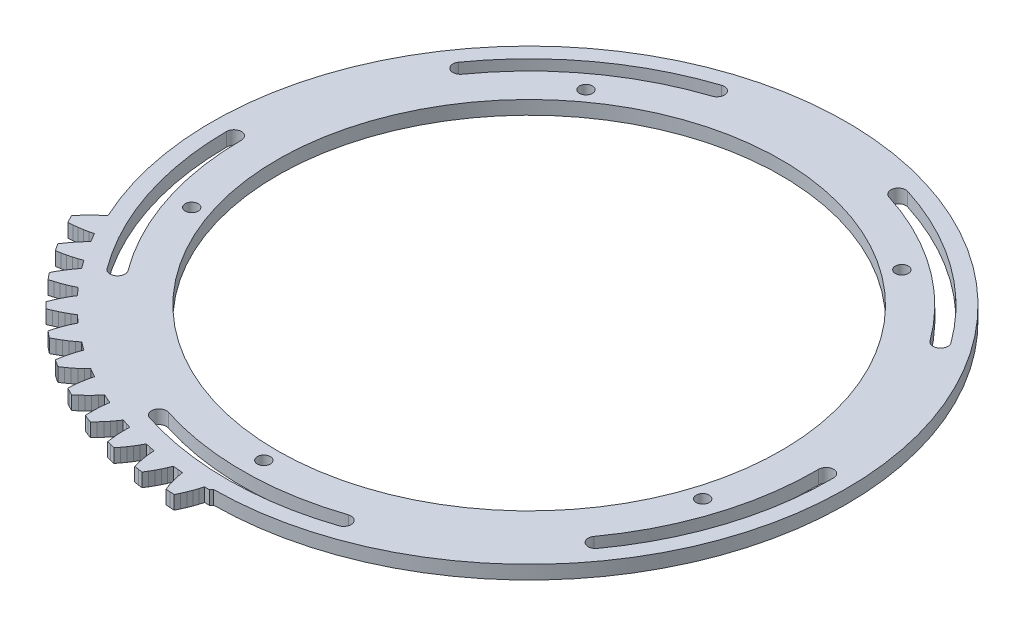
SolidWorks part; units mm, degrees
ref_plane "Front Plane" through (0, 0, 0) normal (0, 0, 1) x (1, 0, 0)
ref_plane "Top Plane" through (0, 0, 0) normal (0, 1, 0) x (1, 0, 0)
ref_plane "Right Plane" through (0, 0, 0) normal (1, 0, 0) x (0, 0, -1)
sketch "Sketch1" plane through (0, 0, 0) normal (0, 1, 0) x (1, 0, 0)
  line L0 (-111.5454, -37.0091) -> (0, 0) construction
  line L1 (0, 0) -> (-76.7897, 104.3262) construction
  line L2 (0, 0) -> (75.4908, 105.2699) construction
  line L3 (0, 0) -> (123.4456, -39.2658) construction
  line L4 (0, 0) -> (0.8028, -129.5375) construction
  circle A0 centre (0, 0) radius 139.7
  circle A1 centre (0, 0) radius 110.9007
  arc A2 (-129.5393, -0.4293) -> (-104.1044, -77.0902) centre (0, 0) ccw construction
  arc A3 (-132.8393, -0.4403) -> (-106.7564, -79.054) centre (0, 0) ccw
  arc A4 (-126.2393, -0.4184) -> (-101.4523, -75.1263) centre (0, 0) ccw
  arc A5 (-126.2393, -0.4184) -> (-132.8393, -0.4403) centre (-129.5393, -0.4293) ccw
  arc A6 (-106.7564, -79.054) -> (-101.4523, -75.1263) centre (-104.1044, -77.0902) ccw
  arc A7 (-40.4381, 123.0665) -> (-105.4871, 75.187) centre (0, 0) ccw construction
  arc A8 (-41.4683, 126.2016) -> (-108.1744, 77.1023) centre (0, 0) ccw
  arc A9 (-39.408, 119.9314) -> (-102.7999, 73.2716) centre (0, 0) ccw
  arc A10 (-39.408, 119.9314) -> (-41.4683, 126.2016) centre (-40.4381, 123.0665) ccw
  arc A11 (-108.1744, 77.1023) -> (-102.7999, 73.2716) centre (-105.4871, 75.187) ccw
  arc A12 (104.5471, 76.4886) -> (38.9097, 123.5583) centre (0, 0) ccw construction
  arc A13 (107.2105, 78.4371) -> (39.9009, 126.7059) centre (0, 0) ccw
  arc A14 (101.8838, 74.5401) -> (37.9185, 120.4106) centre (0, 0) ccw
  arc A15 (101.8838, 74.5401) -> (107.2105, 78.4371) centre (104.5471, 76.4886) ccw
  arc A16 (39.9009, 126.7059) -> (37.9185, 120.4106) centre (38.9097, 123.5583) ccw
  arc A17 (105.0518, -75.794) -> (129.5347, 1.1763) centre (0, 0) ccw construction
  arc A18 (107.728, -77.7248) -> (132.8345, 1.2062) centre (0, 0) ccw
  arc A19 (102.3757, -73.8631) -> (126.2348, 1.1463) centre (0, 0) ccw
  arc A20 (102.3757, -73.8631) -> (107.728, -77.7248) centre (105.0518, -75.794) ccw
  arc A21 (132.8345, 1.2062) -> (126.2348, 1.1463) centre (129.5347, 1.1763) ccw
  arc A22 (-39.6215, -123.3319) -> (41.1471, -122.8313) centre (0, 0) ccw construction
  arc A23 (-40.6309, -126.4737) -> (42.1953, -125.9604) centre (0, 0) ccw
  arc A24 (-38.6122, -120.19) -> (40.0989, -119.7022) centre (0, 0) ccw
  arc A25 (-38.6122, -120.19) -> (-40.6309, -126.4737) centre (-39.6215, -123.3319) ccw
  arc A26 (42.1953, -125.9604) -> (40.0989, -119.7022) centre (41.1471, -122.8313) ccw
  circle A27 centre (-111.5454, -37.0091) radius 2.8585
  circle A28 centre (-69.6672, 94.6496) radius 2.8585
  circle A29 centre (68.4887, 95.5058) radius 2.8585
  circle A30 centre (111.9956, -35.6238) radius 2.8585
  circle A31 centre (0.7283, -117.5225) radius 2.8585
  point P6 (-122.9494, -40.7928)
  point P15 (-76.7897, 104.3262)
  point P22 (75.4908, 105.2699)
  point P29 (123.4456, -39.2658)
  point P36 (0.8028, -129.5375)
  point P41 (0, 0)
  point P55 (0, 0)
  dimension "D2" = 5
extrude "Boss-Extrude1" add sketch "Sketch1" along normal blind 6
sketch "Sketch3" plane through (0, 0, 0) normal (0, 1, 0) x (1, 0, 0)
  line L0 (-95.7738, -103.0452) -> (-97.4797, -104.1074)
  line L1 (-97.4797, -104.1074) -> (-99.2611, -105.0958)
  line L2 (-99.2611, -105.0958) -> (-101.1089, -106.0174)
  line L3 (-101.1089, -106.0174) -> (-103.0168, -106.8763)
  line L4 (-103.0168, -106.8763) -> (-104.9804, -107.6753)
  line L5 (-104.9804, -107.6753) -> (-106.3364, -106.3364)
  line L6 (-106.3364, -106.3364) -> (-107.6753, -104.9804)
  line L7 (-107.6753, -104.9804) -> (-106.8763, -103.0168)
  line L8 (-106.8763, -103.0168) -> (-106.0174, -101.1089)
  line L9 (-106.0174, -101.1089) -> (-105.0958, -99.2611)
  line L10 (-105.0958, -99.2611) -> (-104.1074, -97.4797)
  line L11 (-104.1074, -97.4797) -> (-103.0452, -95.7738)
  line L12 (-103.0452, -95.7738) -> (-104.5458, -94.1335)
  line L13 (-104.5458, -94.1335) -> (-106.0202, -92.4697)
  line L14 (-106.0202, -92.4697) -> (-107.8279, -93.3477)
  line L15 (-107.8279, -93.3477) -> (-109.7028, -94.1445)
  line L16 (-109.7028, -94.1445) -> (-111.6368, -94.8678)
  line L17 (-111.6368, -94.8678) -> (-113.6241, -95.5226)
  line L18 (-113.6241, -95.5226) -> (-115.6604, -96.112)
  line L19 (-115.6604, -96.112) -> (-116.869, -94.6387)
  line L20 (-116.869, -94.6387) -> (-118.0589, -93.1501)
  line L21 (-118.0589, -93.1501) -> (-117.059, -91.2809)
  line L22 (-117.059, -91.2809) -> (-116.0054, -89.4731)
  line L23 (-116.0054, -89.4731) -> (-114.8957, -87.7319)
  line L24 (-114.8957, -87.7319) -> (-113.7265, -86.0635)
  line L25 (-113.7265, -86.0635) -> (-112.4918, -84.4779)
  line L26 (-112.4918, -84.4779) -> (-113.8127, -82.6898)
  line L27 (-113.8127, -82.6898) -> (-115.1052, -80.881)
  line L28 (-115.1052, -80.881) -> (-116.9947, -81.5653)
  line L29 (-116.9947, -81.5653) -> (-118.9427, -82.1617)
  line L30 (-118.9427, -82.1617) -> (-120.9416, -82.6789)
  line L31 (-120.9416, -82.6789) -> (-122.9865, -83.1224)
  line L32 (-122.9865, -83.1224) -> (-125.0733, -83.4957)
  line L33 (-125.0733, -83.4957) -> (-126.1212, -81.9041)
  line L34 (-126.1212, -81.9041) -> (-127.149, -80.2994)
  line L35 (-127.149, -80.2994) -> (-125.9592, -78.5448)
  line L36 (-125.9592, -78.5448) -> (-124.7224, -76.8571)
  line L37 (-124.7224, -76.8571) -> (-123.4368, -75.2414)
  line L38 (-123.4368, -75.2414) -> (-122.0996, -73.7044)
  line L39 (-122.0996, -73.7044) -> (-120.7059, -72.2565)
  line L40 (-120.7059, -72.2565) -> (-121.8327, -70.3401)
  line L41 (-121.8327, -70.3401) -> (-122.929, -68.4061)
  line L42 (-122.929, -68.4061) -> (-124.8797, -68.8891)
  line L43 (-124.8797, -68.8891) -> (-126.8793, -69.2787)
  line L44 (-126.8793, -69.2787) -> (-128.9214, -69.5842)
  line L45 (-128.9214, -69.5842) -> (-131.0014, -69.8114)
  line L46 (-131.0014, -69.8114) -> (-133.1158, -69.9646)
  line L47 (-133.1158, -69.9646) -> (-133.9916, -68.2722)
  line L48 (-133.9916, -68.2722) -> (-134.846, -66.5688)
  line L49 (-134.846, -66.5688) -> (-133.4793, -64.9482)
  line L50 (-133.4793, -64.9482) -> (-132.0729, -63.3991)
  line L51 (-132.0729, -63.3991) -> (-130.6254, -61.9265)
  line L52 (-130.6254, -61.9265) -> (-129.1349, -60.5378)
  line L53 (-129.1349, -60.5378) -> (-127.5975, -59.2435)
  line L109 (0, -140.6803) -> (2.9817, -137.1267)
  line L110 (-97.4797, -91.2809) -> (-36.7464, -131.8002)
  line L111 (-97.4797, -91.2809) -> (-126.1069, -57.3357)
  line L112 (-126.1069, -57.3357) -> (-127.5975, -59.2435)
  line L115 (-36.7464, -131.8002) -> (2.9817, -137.1267)
  line L741 (0, -140.6803) -> (-2.2231, -140.6627)
  line L742 (-2.2231, -140.6627) -> (-2.7801, -142.5936)
  line L743 (-2.7801, -142.5936) -> (-3.4425, -144.5201)
  line L744 (-3.4425, -144.5201) -> (-4.199, -146.4413)
  line L745 (-4.199, -146.4413) -> (-5.0422, -148.3562)
  line L746 (-5.0422, -148.3562) -> (-5.9668, -150.2639)
  line L747 (-5.9668, -150.2639) -> (-7.8704, -150.1762)
  line L748 (-7.8704, -150.1762) -> (-9.7727, -150.0645)
  line L749 (-9.7727, -150.0645) -> (-10.4929, -148.0706)
  line L750 (-10.4929, -148.0706) -> (-10.5564, -148.1519)
  line L751 (-10.5564, -148.1519) -> (-11.6828, -144.0882)
  line L752 (-11.6828, -144.0882) -> (-12.1402, -142.103)
  line L753 (-12.1402, -142.103) -> (-12.4924, -140.1245)
  line L754 (-12.4924, -140.1245) -> (-14.7051, -139.9096)
  line L755 (-14.7051, -139.9096) -> (-16.9141, -139.6597)
  line L756 (-16.9141, -139.6597) -> (-17.67, -141.5218)
  line L757 (-17.67, -141.5218) -> (-18.5301, -143.3686)
  line L758 (-18.5301, -143.3686) -> (-19.4833, -145.2002)
  line L759 (-19.4833, -145.2002) -> (-20.522, -147.0165)
  line L760 (-20.522, -147.0165) -> (-21.641, -148.817)
  line L761 (-21.641, -148.817) -> (-23.525, -148.5309)
  line L762 (-23.525, -148.5309) -> (-25.4052, -148.2208)
  line L763 (-25.4052, -148.2208) -> (-25.9129, -146.1626)
  line L764 (-25.9129, -146.1626) -> (-26.3396, -144.1142)
  line L765 (-26.3396, -144.1142) -> (-26.6801, -142.0777)
  line L766 (-26.6801, -142.0777) -> (-26.9275, -140.0556)
  line L767 (-26.9275, -140.0556) -> (-27.0709, -138.0511)
  line L768 (-27.0709, -138.0511) -> (-29.2491, -137.606)
  line L769 (-29.2491, -137.606) -> (-31.4199, -137.1267)
  line L770 (-31.4199, -137.1267) -> (-32.3662, -138.8995)
  line L771 (-32.3662, -138.8995) -> (-33.4147, -140.6462)
  line L772 (-33.4147, -140.6462) -> (-34.5541, -142.3682)
  line L773 (-34.5541, -142.3682) -> (-35.777, -144.066)
  line L774 (-35.777, -144.066) -> (-37.078, -145.7397)
  line L775 (-37.078, -145.7397) -> (-38.9218, -145.2582)
  line L776 (-38.9218, -145.2582) -> (-40.7593, -144.7533)
  line L777 (-40.7593, -144.7533) -> (-41.0492, -142.6533)
  line L778 (-41.0492, -142.6533) -> (-41.2593, -140.5715)
  line L779 (-41.2593, -140.5715) -> (-41.3851, -138.5106)
  line L780 (-41.3851, -138.5106) -> (-41.4198, -136.4736)
  line L781 (-41.4198, -136.4736) -> (-41.3529, -134.4651)
  line L782 (-41.3529, -134.4651) -> (-43.4726, -133.7949)
  line L783 (-43.4726, -133.7949) -> (-45.5814, -133.0912)
  line L784 (-45.5814, -133.0912) -> (-46.7079, -134.7554)
  line L785 (-46.7079, -134.7554) -> (-47.9332, -136.3829)
  line L786 (-47.9332, -136.3829) -> (-49.2464, -137.9764)
  line L787 (-49.2464, -137.9764) -> (-50.64, -139.537)
  line L788 (-50.64, -139.537) -> (-52.1089, -141.0656)
  line L789 (-52.1089, -141.0656) -> (-53.8922, -140.394)
  line L790 (-53.8922, -140.394) -> (-55.6669, -139.6998)
  line L791 (-55.6669, -139.6998) -> (-55.7356, -137.581)
  line L792 (-55.7356, -137.581) -> (-55.727, -135.4887)
  line L793 (-55.727, -135.4887) -> (-55.6367, -133.4259)
  line L794 (-55.6367, -133.4259) -> (-55.4583, -131.3965)
  line L795 (-55.4583, -131.3965) -> (-55.1818, -129.4059)
  line L796 (-55.1818, -129.4059) -> (-57.2198, -128.5178)
  line L797 (-57.2198, -128.5178) -> (-59.2435, -127.5975)
  line L798 (-59.2435, -127.5975) -> (-60.5378, -129.1349)
  line L799 (-60.5378, -129.1349) -> (-61.9265, -130.6254)
  line L800 (-61.9265, -130.6254) -> (-63.3991, -132.0729)
  line L801 (-63.3991, -132.0729) -> (-64.9482, -133.4793)
  line L802 (-64.9482, -133.4793) -> (-66.5688, -134.846)
  line L803 (-66.5688, -134.846) -> (-68.2722, -133.9916)
  line L804 (-68.2722, -133.9916) -> (-69.9646, -133.1158)
  line L805 (-69.9646, -133.1158) -> (-69.8114, -131.0014)
  line L806 (-69.8114, -131.0014) -> (-69.5842, -128.9214)
  line L807 (-69.5842, -128.9214) -> (-69.2787, -126.8793)
  line L808 (-69.2787, -126.8793) -> (-68.8891, -124.8797)
  line L809 (-68.8891, -124.8797) -> (-68.4061, -122.929)
  line L810 (-68.4061, -122.929) -> (-70.3401, -121.8327)
  line L811 (-70.3401, -121.8327) -> (-72.2565, -120.7059)
  line L812 (-72.2565, -120.7059) -> (-73.7044, -122.0996)
  line L813 (-73.7044, -122.0996) -> (-75.2414, -123.4368)
  line L814 (-75.2414, -123.4368) -> (-76.8571, -124.7224)
  line L815 (-76.8571, -124.7224) -> (-78.5448, -125.9592)
  line L816 (-78.5448, -125.9592) -> (-80.2994, -127.149)
  line L817 (-80.2994, -127.149) -> (-81.9041, -126.1212)
  line L818 (-81.9041, -126.1212) -> (-83.4957, -125.0733)
  line L819 (-83.4957, -125.0733) -> (-83.1224, -122.9865)
  line L820 (-83.1224, -122.9865) -> (-82.6789, -120.9416)
  line L821 (-82.6789, -120.9416) -> (-82.1617, -118.9427)
  line L822 (-82.1617, -118.9427) -> (-81.5653, -116.9947)
  line L823 (-81.5653, -116.9947) -> (-80.881, -115.1052)
  line L824 (-80.881, -115.1052) -> (-82.6898, -113.8127)
  line L825 (-82.6898, -113.8127) -> (-84.4779, -112.4918)
  line L826 (-84.4779, -112.4918) -> (-86.0635, -113.7265)
  line L827 (-86.0635, -113.7265) -> (-87.7319, -114.8957)
  line L828 (-87.7319, -114.8957) -> (-89.4731, -116.0054)
  line L829 (-89.4731, -116.0054) -> (-91.2809, -117.059)
  line L830 (-91.2809, -117.059) -> (-93.1501, -118.0589)
  line L831 (-93.1501, -118.0589) -> (-94.6387, -116.869)
  line L832 (-94.6387, -116.869) -> (-96.112, -115.6604)
  line L833 (-96.112, -115.6604) -> (-95.5226, -113.6241)
  line L834 (-95.5226, -113.6241) -> (-94.8678, -111.6368)
  line L835 (-94.8678, -111.6368) -> (-94.1445, -109.7028)
  line L836 (-94.1445, -109.7028) -> (-93.3477, -107.8279)
  line L837 (-93.3477, -107.8279) -> (-92.4697, -106.0202)
  line L838 (-92.4697, -106.0202) -> (-94.1335, -104.5458)
  line L839 (-94.1335, -104.5458) -> (-95.7738, -103.0452)
extrude "Boss-Extrude2" add sketch "Sketch3" along normal blind 6
